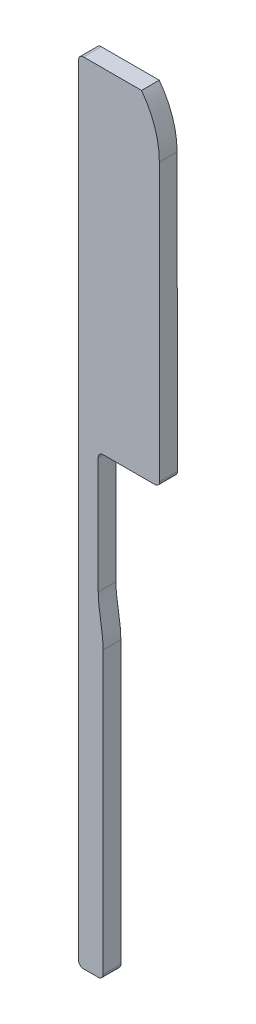
SolidWorks part; units mm, degrees
ref_plane "Płaszczyzna przednia" through (0, 0, 0) normal (0, 0, 1) x (1, 0, 0)
ref_plane "Płaszczyzna górna" through (0, 0, 0) normal (0, 1, 0) x (1, 0, 0)
ref_plane "Płaszczyzna prawa" through (0, 0, 0) normal (1, 0, 0) x (0, 0, -1)
sketch "Sketch1" plane through (0, 0, 0) normal (0, 0, 1) x (1, 0, 0)
  line L0 (0, 4.5) -> (0, 6.5)
  line L1 (0, 0) -> (18.25, 0) construction
  line L2 (0, 0) -> (0, 83.5) construction
  line L3 (0, 83.5) -> (18.25, 83.5) construction
  line L4 (18.25, 0) -> (18.25, 83.5) construction
  line L5 (0, 6.5) -> (6.1, 6.5)
  line L6 (6.1, 6.5) -> (6.1, 10.5)
  line L7 (6.1, 10.5) -> (10, 14.4)
  line L8 (10, 14.4) -> (10, 83.5)
  line L9 (10, 83.5) -> (16.4, 83.5)
  line L10 (18.2123, 78.0955) -> (18.25, 49.5)
  line L11 (18.25, 49.5) -> (12, 49.5)
  line L12 (12, 49.5) -> (12, 37.18)
  line L13 (12, 35.24) -> (12, 39.1406) construction
  line L14 (12.5, 32.33) -> (12.5, 3.07)
  line L15 (12.5, 31.0162) -> (12.5, 33.6438) construction
  arc A0 (16.4, 83.5) -> (18.2123, 78.0955) centre (9.2123, 78.0836) cw
  arc A1 (12.5, 3.07) -> (9.43, 0) centre (9.43, 3.07) cw
  arc A2 (9.43, 0) -> (0, 4.5) centre (9.43, 12.1305) cw
  spline S0 degree 3 poles (12, 37.18) (12, 35.5548) (12.5, 33.9723) (12.5, 32.33) knots 0 0 0 0 1 1 1 1
  point P5 (16.4, 83.5)
  point P6 (0, 6.5)
  point P7 (0, 4.5)
  point P8 (18.25, 49.5)
  dimension "D11" = 9
  dimension "D1" = 83.5
  dimension "D2" = 18.25
  dimension "D3" = 1.85
  dimension "D4" = 34
  dimension "D5" = 4.5
  dimension "D6" = 2
  dimension "D7" = 6.1
  dimension "D8" = 4
  dimension "D9" = 45
  dimension "D10" = 3.9
  dimension "D12" = 6.25
  dimension "D13" = 12.32
  dimension "D14" = 29.26
  dimension "D15" = 4.85
extrude "Boss-Extrude1" add sketch "Sketch1" along normal blind 1.8
fillet "Fillet1" radius 0.5 7 edges at (0, 6.5, 0.9) (6.1, 6.5, 0.9) (6.1, 10.5, 0.9) (10, 14.4, 0.9) (18.25, 49.5, 0.9) (10, 83.5, 0.9) (12, 49.5, 0.9)
sketch "Sketch5" plane through (0, 0, 0) normal (0, 0, -1) x (-1, 0, 0)
  line L0 (-12.5, 3.07) -> (-12.5, 32.33) construction
  line L1 (-7, -2.4998) -> (-7, 0.5002)
  line L2 (-7, 0.5002) -> (-11, 0.5002)
  line L3 (-11, 0.5002) -> (-11.824, -1.5785)
  circle A0 centre (-9.5, -2.4998) radius 2.5
  arc A1 (-9.43, 0) -> (0, 4.5) centre (-9.43, 12.1305) ccw construction
  circle A2 centre (-9.5, -2.4998) radius 1.75
  arc M20 (-12.5, 3.07) -> (-9.43, 0) centre (-9.43, 3.07) ccw
  arc M21 (-9.43, 0) -> (0, 4.5) centre (-9.43, 12.1305) ccw
  dimension "D1" = 5
  dimension "D5" = 3.5
  dimension "D2" = 3
  dimension "D3" = 3
  dimension "D4" = 4
extrude "Boss-Extrude2" add sketch "Sketch5" against normal blind 1.8 contours A0 A2 | A0 L1 L3 M21 M20 | L2 L3 L1 M20 M21
fillet "Fillet2" radius 1 2 edges at (7, 0.2459, 0.9) (11.0219, 0.445, 0.9)
sketch "Sketch6" plane through (0, 0, 1.8) normal (0, 0, 1) x (1, 0, 0)
  line L0 (10, 23.1707) -> (10, 3.27)
  line L1 (10, 83) -> (10, 14.6071) construction
  line L2 (10, 3.27) -> (15.0719, 3.27)
  line L3 (15.0719, 3.27) -> (15.0719, -7.8988)
  line L4 (15.0719, -7.8988) -> (-3.497, -7.8988)
  line L5 (-3.497, -7.8988) -> (-3.497, 23.1707)
  line L6 (-3.497, 23.1707) -> (10, 23.1707)
  dimension "D1" = 0.2
extrude "Cut-Extrude1" cut sketch "Sketch6" against normal through all
fillet "Fillet3" radius 0.5 2 edges at (10, 3.27, 0.9) (12.5, 3.27, 0.9)
